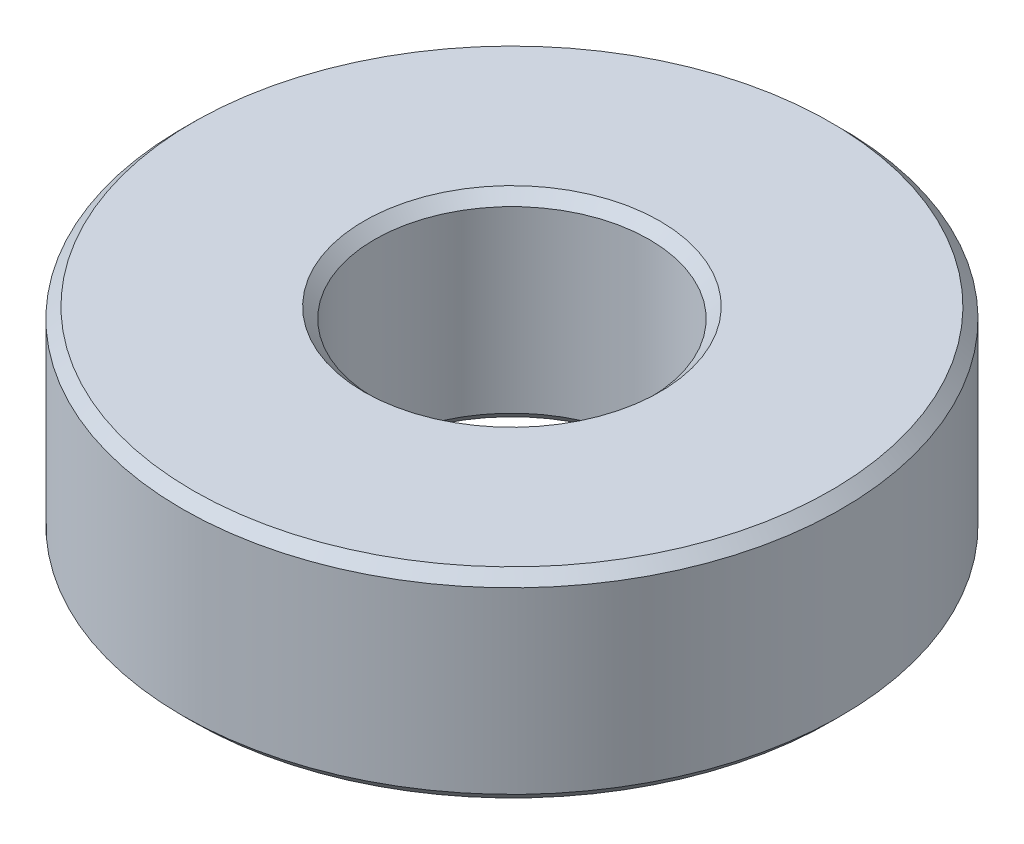
SolidWorks part; units mm, degrees
ref_plane "Front" through (0, 0, 0) normal (0, 0, 1) x (1, 0, 0)
ref_plane "Top" through (0, 0, 0) normal (0, 1, 0) x (1, 0, 0)
ref_plane "Right" through (0, 0, 0) normal (1, 0, 0) x (0, 0, -1)
sketch "Sketch1" plane through (0, 0, 0) normal (0, 1, 0) x (1, 0, 0)
  circle A0 centre (0, 0) radius 7.8613
  circle A1 centre (0, 0) radius 3.2766
  dimension "D1" = 15.7226
  dimension "D2" = 6.5532
extrude "Boss-Extrude1" add sketch "Sketch1" along normal blind 4.7752
chamfer "Chamfer1" distance 0.254 angle 45 4 edges at (0, 0, 3.2766) (0, 0, 7.8613) (0, 4.7752, 3.2766) (0, 4.7752, 7.8613)
